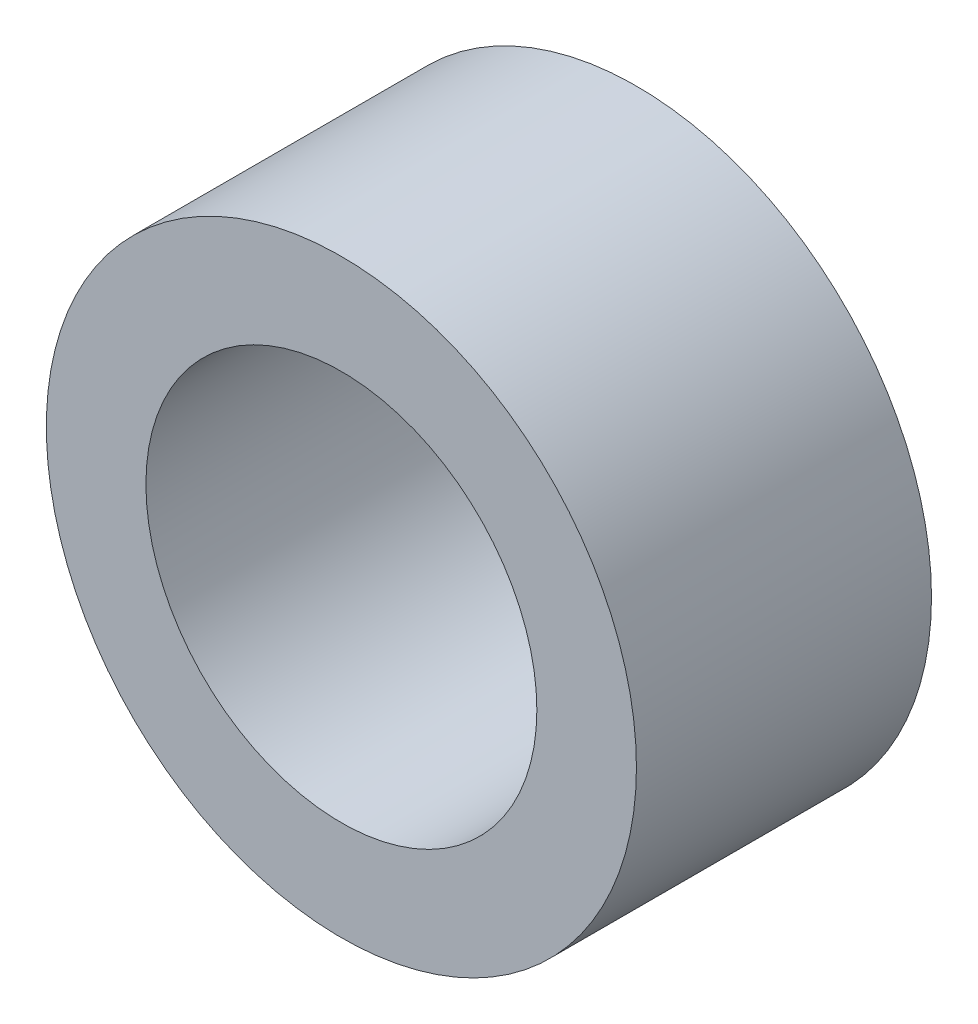
SolidWorks part; units mm, degrees
ref_plane "Front Plane" through (0, 0, 0) normal (0, 0, 1) x (1, 0, 0)
ref_plane "Top Plane" through (0, 0, 0) normal (0, 1, 0) x (1, 0, 0)
ref_plane "Right Plane" through (0, 0, 0) normal (1, 0, 0) x (0, 0, -1)
sketch "Sketch1" plane through (0, 0, 0) normal (0, 0, 1) x (1, 0, 0)
  circle A0 centre (0, 0) radius 4
  circle A1 centre (0, 0) radius 2.65
  dimension "OD" = 8
  dimension "ID" = 5.3
extrude "Extrude1" add sketch "Sketch1" along normal mid plane 4
sketch "Sketch2" plane through (0, 0, 0) normal (1, 0, 0) x (0, 0, -1)
  line L0 (-2, -2.65) -> (2, -2.65) construction
  line L3 (2, 2.65) -> (-2, 2.65) construction
  line L5 (-2, -2.65) -> (2, -2.65)
  line L6 (2, 2.65) -> (-2, 2.65)
sketch "Sketch4" plane through (0, 0, 2) normal (0, 0, 1) x (1, 0, 0)
  line L0 (0, 0) -> (-1.8738, 1.8738)
  line L1 (0, -1.1) -> (0, 1.1) construction
  circle A0 centre (0, 0) radius 2.65 construction
  dimension "D1" = 45
